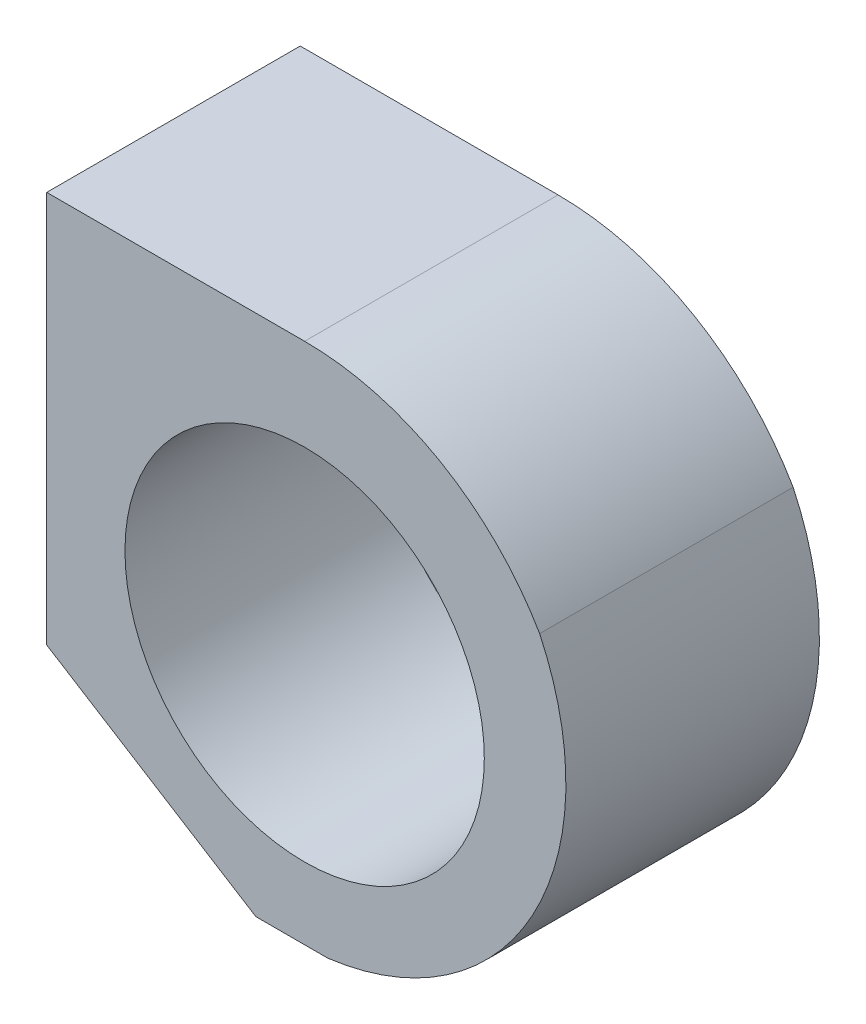
SolidWorks part; units mm, degrees
ref_plane "Front" through (0, 0, 0) normal (0, 0, 1) x (1, 0, 0)
ref_plane "Top" through (0, 0, 0) normal (0, 1, 0) x (1, 0, 0)
ref_plane "Right" through (0, 0, 0) normal (1, 0, 0) x (0, 0, -1)
sketch "Sketch2" plane through (0, 0, 0) normal (0, 0, 1) x (1, 0, 0)
  line L0 (42.0767, 4.0091) -> (59.1767, 4.0091) construction
  line L1 (-28.6766, -10.1263) -> (-11.5766, -10.1263) construction
  line L2 (-12.3146, -4.0934) -> (4.7854, -4.0934) construction
  line L3 (-30.1193, 84.0985) -> (14.0483, 84.0985) construction
  line L4 (0, 0) -> (17.1, 0) construction
  line L5 (17.1, 0) -> (17.1, -15.5) construction
  line L6 (-19.7386, 20.7672) -> (-19.7386, -9.2328)
  line L7 (-19.7386, 20.7672) -> (0, 20.7672)
  line L8 (0, 20.7672) -> (0, 0) construction
  line L9 (17.9849, 10.3836) -> (0, 0) construction
  line L10 (-3.7353, -19.2328) -> (-19.7386, -9.2328)
  line L11 (-3.7353, -19.2328) -> (1.7737, -19.2328)
  circle A2 centre (17.1, -15.5) radius 1.8 construction
  circle A3 centre (-17.7, -15.5731) radius 1.8 construction
  circle A4 centre (17.1, 18.5) radius 1.8 construction
  arc A5 (0, 20.7672) -> (17.9849, 10.3836) centre (0, 0) cw
  arc A6 (17.9849, 10.3836) -> (1.7737, -19.2328) centre (-0.8551, 1.4511) cw
  circle A9 centre (0, 0) radius 13.75
extrude "Boss-Extrude1" add sketch "Sketch2" along normal blind 19.4
